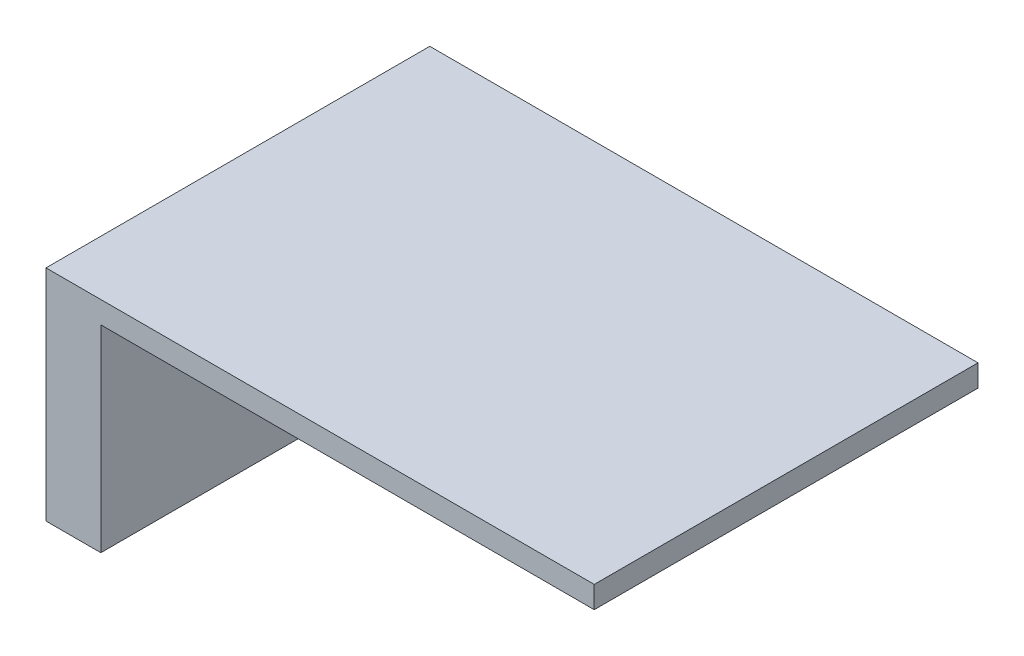
SolidWorks part; units mm, degrees
ref_plane "Front" through (0, 0, 0) normal (0, 0, 1) x (1, 0, 0)
ref_plane "Top" through (0, 0, 0) normal (0, 1, 0) x (1, 0, 0)
ref_plane "Right" through (0, 0, 0) normal (1, 0, 0) x (0, 0, -1)
sketch "Sketch1" plane through (0, 0, 0) normal (0, 0, 1) x (1, 0, 0)
  line L0 (0, 0) -> (0, 10)
  line L1 (0, 10) -> (25, 10)
  line L2 (25, 10) -> (25, 9)
  line L3 (25, 9) -> (2.5, 9)
  line L4 (2.5, 9) -> (2.5, 0)
  line L5 (2.5, 0) -> (0, 0)
  dimension "D1" = 10
  dimension "D2" = 25
  dimension "D3" = 1
  dimension "D4" = 2.5
extrude "Boss-Extrude1" add sketch "Sketch1" along normal blind 17.5
sketch "Sketch2" plane through (0, 10, 0) normal (0, 1, 0) x (1, 0, 0)
  line L0 (0, -8.75) -> (25, -8.75) construction
  line L1 (0, -17.5) -> (0, 0) construction
  line L2 (25, -17.5) -> (25, 0) construction
